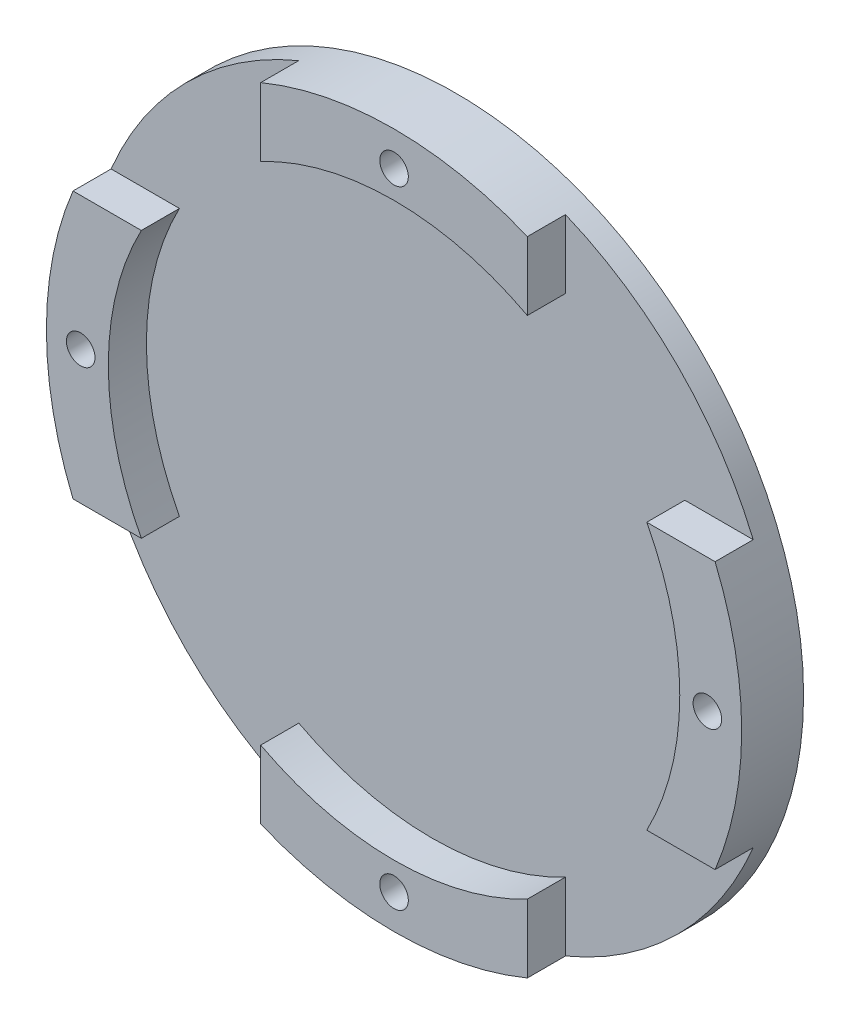
SolidWorks part; units mm, degrees
ref_plane "前视基准面" through (0, 0, 0) normal (0, 0, 1) x (1, 0, 0)
ref_plane "上视基准面" through (0, 0, 0) normal (0, 1, 0) x (1, 0, 0)
ref_plane "右视基准面" through (0, 0, 0) normal (1, 0, 0) x (0, 0, -1)
other "Configuration Table"
sketch "草图1" plane through (0, 0, 0) normal (0, 0, 1) x (1, 0, 0)
  circle A0 centre (0, 0) radius 36.5
  dimension "D1" = 73
extrude "凸台-拉伸1" add sketch "草图1" along normal blind 6.5
sketch "草图3" plane through (0, 0, 6.5) normal (0, 0, 1) x (1, 0, 0)
  line L0 (0, -30) -> (0, -36.5) construction
  line L1 (-14, -26.533) -> (-14, -33.7083)
  line L2 (14, -26.533) -> (14, -33.7083)
  line L3 (0, -30) -> (0, 0) construction
  line L4 (-14, -26.533) -> (14, -26.533) construction
  line L5 (-26.533, 14) -> (-33.7083, 14)
  line L6 (-26.533, -14) -> (-33.7083, -14)
  line L7 (14, 26.533) -> (14, 33.7083)
  line L8 (-14, 26.533) -> (-14, 33.7083)
  line L9 (26.533, -14) -> (33.7083, -14)
  line L10 (26.533, 14) -> (33.7083, 14)
  circle A0 centre (0, 0) radius 30
  circle A1 centre (0, 0) radius 36.5 construction
  arc A2 (-14, -26.533) -> (14, -26.533) centre (0, 0) ccw
  arc A3 (-14, -33.7083) -> (14, -33.7083) centre (0, 0) ccw
  circle A4 centre (0, 0) radius 30
  arc A5 (-33.7083, 14) -> (-33.7083, -14) centre (0, 0) ccw
  arc A6 (-26.533, 14) -> (-26.533, -14) centre (0, 0) ccw
  circle A7 centre (0, 0) radius 30
  arc A8 (14, 33.7083) -> (-14, 33.7083) centre (0, 0) ccw
  arc A9 (14, 26.533) -> (-14, 26.533) centre (0, 0) ccw
  circle A10 centre (0, 0) radius 30
  arc A11 (33.7083, -14) -> (33.7083, 14) centre (0, 0) ccw
  arc A12 (26.533, -14) -> (26.533, 14) centre (0, 0) ccw
  arc A13 (-33.7083, -14) -> (-14, -33.7083) centre (0, 0) ccw
  arc A14 (14, 33.7083) -> (33.7083, 14) centre (0, 0) cw
  arc A15 (33.7083, -14) -> (14, -33.7083) centre (0, 0) cw
  arc A16 (-14, 33.7083) -> (-33.7083, 14) centre (0, 0) ccw
  arc A17 (-14, 26.533) -> (-26.533, 14) centre (0, 0) ccw
  arc A18 (14, 26.533) -> (26.533, 14) centre (0, 0) cw
  arc A19 (26.533, -14) -> (14, -26.533) centre (0, 0) cw
  arc A20 (-26.533, -14) -> (-14, -26.533) centre (0, 0) ccw
  point P32 (0, 0)
  circle M4 centre (0, 0) radius 36.5
  dimension "D1" = 60
  dimension "D2" = 28
  dimension "D3" = 4
extrude "切除-拉伸2" cut sketch "草图3" against normal blind 4 contours A0 L10 L7 M4 | A0 L2 L9 M4 | A0 L6 L1 M4 | A0 L8 L5 M4
sketch "草图4" plane through (0, 0, 6.5) normal (0, 0, 1) x (1, 0, 0)
  circle A0 centre (0, 0) radius 30
  arc M2 (-14, 26.533) -> (-26.533, 14) centre (0, 0) ccw
  arc M6 (-26.533, -14) -> (-14, -26.533) centre (0, 0) ccw
  arc M10 (14, -26.533) -> (26.533, -14) centre (0, 0) ccw
  arc M14 (26.533, 14) -> (14, 26.533) centre (0, 0) ccw
  dimension "D1" = 60
extrude "切除-拉伸3" cut sketch "草图4" against normal blind 4 contours A0 M14 M2 M6 M10
sketch "草图6" plane through (0, 0, 0) normal (0, 0, -1) x (-1, 0, 0)
  line L0 (0, 0) -> (-32.9, 0) construction
  circle A0 centre (0, 0) radius 32.9 construction
  circle A1 centre (0, 32.9) radius 1.5
  circle A2 centre (32.9, 0) radius 1.5
  circle A3 centre (0, -32.9) radius 1.5
  circle A4 centre (-32.9, 0) radius 1.5
  point P14 (0, 0)
  dimension "D1" = 65.8
  dimension "D2" = 3
  dimension "D4" = 32.9
  dimension "D3" = 4
extrude "切除-拉伸5" cut sketch "草图6" against normal through all contours A2 | A3 | A1 | A4
sketch "草图7" plane through (0, 0, 0) normal (0, 0, -1) x (-1, 0, 0)
  circle A1 centre (0, 0) radius 36.5
  dimension "D1" = 73
sketch "草图8" plane through (0, 0, 0) normal (0, 0, -1) x (-1, 0, 0)
  line L0 (0, 0) -> (0, 29.9988) construction
  line L1 (-29.9988, -1.675) -> (-29.9988, 1.675)
  line L2 (-29.9988, 1.675) -> (-32.9, 3.35)
  line L3 (-32.9, 3.35) -> (-35.8012, 1.675)
  line L4 (-35.8012, 1.675) -> (-35.8012, -1.675)
  line L5 (-35.8012, -1.675) -> (-32.9, -3.35)
  line L6 (-32.9, -3.35) -> (-29.9988, -1.675)
  line L7 (1.675, -35.8012) -> (3.35, -32.9)
  line L8 (3.35, -32.9) -> (1.675, -29.9988)
  line L9 (1.675, -29.9988) -> (-1.675, -29.9988)
  line L10 (-1.675, -29.9988) -> (-3.35, -32.9)
  line L11 (-3.35, -32.9) -> (-1.675, -35.8012)
  line L12 (-1.675, -35.8012) -> (1.675, -35.8012)
  line L13 (35.8012, -1.675) -> (35.8012, 1.675)
  line L14 (35.8012, 1.675) -> (32.9, 3.35)
  line L15 (32.9, 3.35) -> (29.9988, 1.675)
  line L16 (29.9988, 1.675) -> (29.9988, -1.675)
  line L17 (29.9988, -1.675) -> (32.9, -3.35)
  line L18 (32.9, -3.35) -> (35.8012, -1.675)
  line L19 (1.675, 29.9988) -> (3.35, 32.9)
  line L20 (3.35, 32.9) -> (1.675, 35.8012)
  line L21 (1.675, 35.8012) -> (-1.675, 35.8012)
  line L22 (-1.675, 35.8012) -> (-3.35, 32.9)
  line L23 (-3.35, 32.9) -> (-1.675, 29.9988)
  line L24 (-1.675, 29.9988) -> (1.675, 29.9988)
  line L25 (0, 0) -> (29.9988, 0) construction
  line L26 (0, 0) -> (-29.9988, 0) construction
  line L27 (0, 0) -> (0, -29.9988) construction
  circle A0 centre (-32.9, 0) radius 2.9012 construction
  circle A1 centre (0, -32.9) radius 2.9012 construction
  circle A2 centre (32.9, 0) radius 2.9012 construction
  circle A3 centre (0, 32.9) radius 2.9012 construction
  dimension "D1" = 3.35
  dimension "D2" = 3.35
  dimension "D3" = 3.35
  dimension "D4" = 3.35
extrude "切除-拉伸6" cut sketch "草图8" against normal blind 2.2
